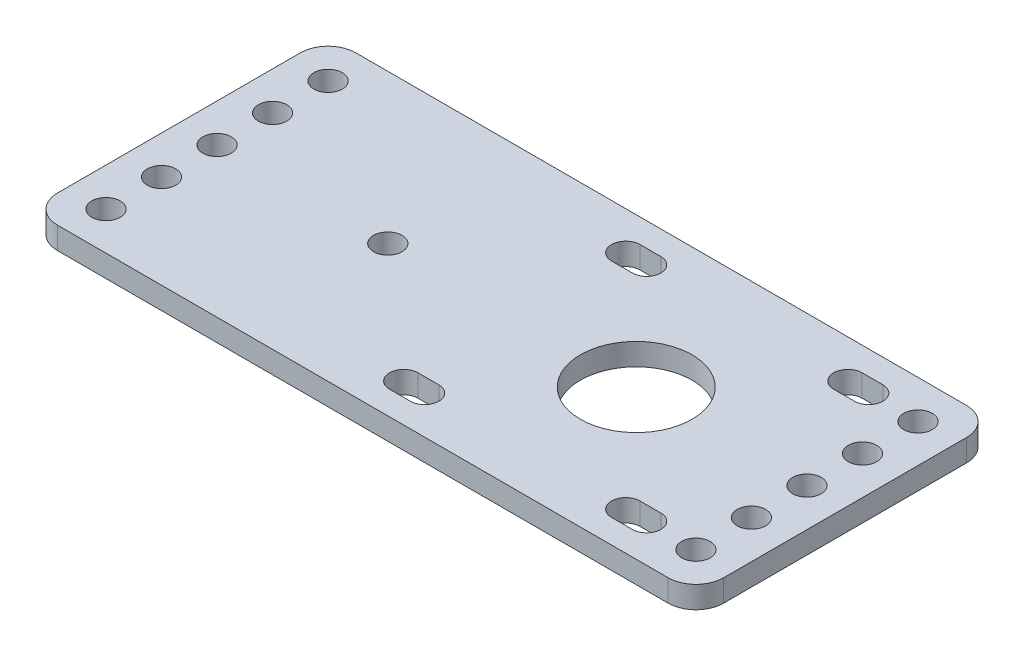
SolidWorks part; units mm, degrees
ref_plane "Front Plane" through (0, 0, 0) normal (0, 0, 1) x (1, 0, 0)
ref_plane "Top Plane" through (0, 0, 0) normal (0, 1, 0) x (1, 0, 0)
ref_plane "Right Plane" through (0, 0, 0) normal (1, 0, 0) x (0, 0, -1)
sketch "Sketch1" plane through (0, 0, 0) normal (0, 1, 0) x (1, 0, 0)
  line L0 (0, 0) -> (50000, 0) construction
  line L1 (48, -21.5) -> (-48, -21.5)
  line L2 (48, -21.5) -> (48, 21.5)
  line L3 (48, 21.5) -> (-48, 21.5)
  line L4 (-48, -21.5) -> (-48, 21.5)
  line L5 (48, -21.5) -> (-48, 21.5) construction
  line L6 (48, 21.5) -> (-48, -21.5) construction
  line L7 (0.4, 18.05) -> (3.4, 18.05)
  line L8 (35.4, -16) -> (0.4, -16) construction
  line L9 (35.4, -16) -> (35.4, 16) construction
  line L10 (35.4, 16) -> (0.4, 16) construction
  line L11 (0.4, -16) -> (0.4, 16) construction
  line L12 (35.4, -16) -> (0.4, 16) construction
  line L13 (35.4, 16) -> (0.4, -16) construction
  line L14 (0.4, 13.95) -> (3.4, 13.95)
  line L15 (17.9, 56.2389) -> (17.9, -49943.7611) construction
  line L16 (0.4, -13.95) -> (3.4, -13.95)
  line L17 (0.4, -18.05) -> (3.4, -18.05)
  line L18 (-42.5, -19.9024) -> (-42.5, -1.0474) construction
  line L19 (35.4, -18.05) -> (32.4, -18.05)
  line L20 (35.4, -13.95) -> (32.4, -13.95)
  line L21 (35.4, 13.95) -> (32.4, 13.95)
  line L22 (35.4, 18.05) -> (32.4, 18.05)
  line L23 (-42.5, 16) -> (-42.5, 8) construction
  line L24 (0, -21.5) -> (0, 49978.5) construction
  circle A0 centre (-17.9, 0) radius 18 construction
  circle A1 centre (17.9, 0) radius 18 construction
  arc A2 (0.4, 18.05) -> (0.4, 13.95) centre (0.4, 16) ccw
  arc A4 (0.4, -18.05) -> (0.4, -13.95) centre (0.4, -16) cw
  arc A5 (3.4, 13.95) -> (3.4, 18.05) centre (3.4, 16) ccw
  arc A6 (3.4, -13.95) -> (3.4, -18.05) centre (3.4, -16) cw
  arc A7 (35.4, -18.05) -> (35.4, -13.95) centre (35.4, -16) ccw
  arc A8 (32.4, -13.95) -> (32.4, -18.05) centre (32.4, -16) ccw
  arc A9 (35.4, 18.05) -> (35.4, 13.95) centre (35.4, 16) cw
  arc A10 (32.4, 13.95) -> (32.4, 18.05) centre (32.4, 16) cw
  circle A11 centre (17.9, 0) radius 8.05
  circle A12 centre (-17.9, 0) radius 2.05
  circle A13 centre (-17.9, 0) radius 19 construction
  circle A14 centre (-42.5, 16) radius 2.05
  circle A15 centre (-42.5, 8) radius 2.05
  circle A16 centre (-42.5, 0) radius 2.05
  circle A17 centre (-42.5, -8) radius 2.05
  circle A18 centre (-42.5, -16) radius 2.05
  circle A19 centre (42.5, 16) radius 2.05
  circle A20 centre (42.5, 8) radius 2.05
  circle A21 centre (42.5, 0) radius 2.05
  circle A22 centre (42.5, -8) radius 2.05
  circle A23 centre (42.5, -16) radius 2.05
  point P0 (0, 0)
  point P57 (0, -21.5)
  dimension "D4" = 36
  dimension "D8" = 4.1
  dimension "D10" = 4.1
  dimension "D11" = 16.1
  dimension "D12" = 38
  dimension "D14" = 4.1
  dimension "D1" = 96
  dimension "D2" = 43
  dimension "D3" = 35.8
  dimension "D5" = 17.9
  dimension "D6" = 35
  dimension "D7" = 32
  dimension "D9" = 3
  dimension "D13" = 5.5
  dimension "D15" = 5.5
  dimension "D17" = 8
  dimension "D16" = 5
extrude "Boss-Extrude1" add sketch "Sketch1" along normal blind 3.175
fillet "Fillet1" radius 4 4 edges at (48, 1.5875, 21.5) (48, 1.5875, -21.5) (-48, 1.5875, -21.5) (-48, 1.5875, 21.5)
equation "\"w\"= 43mm"
equation "\"h\"= 96mm"
equation "\"pitchDiameter\"= 36mm'45 Tooth Hub-Mount Gear"
equation "\"servoBlockLargeCenterDistance\"= 35mm"
equation "\"cent2cent\"= 35.8mm"
equation "\"servoBlockLargeCenterDistanceheight\"= 32mm"
equation "\"sh\"= 4.1mm"
equation "\"D1@Sketch1\"=\"h\""
equation "\"D2@Sketch1\"=\"w\""
equation "\"D4@Sketch1\"=\"pitchDiameter\""
equation "\"D5@Sketch1\"=\"cent2cent\"/2"
equation "\"D6@Sketch1\"=\"servoBlockLargeCenterDistance\""
equation "\"D7@Sketch1\"=\"servoBlockLargeCenterDistanceheight\""
equation "\"D8@Sketch1\"=\"sh\""
equation "\"D9@Sketch1\"=3"
equation "\"bearingOD\"= 14.1mm"
equation "\"thick\"= 3.175mm"
equation "\"D10@Sketch1\"=\"sh\""
equation "\"D11@Sketch1\"=\"bearingOD\"+2"
equation "\"D1@Boss-Extrude1\"=\"thick\""
equation "\"D14@Sketch1\"=\"sh\""
